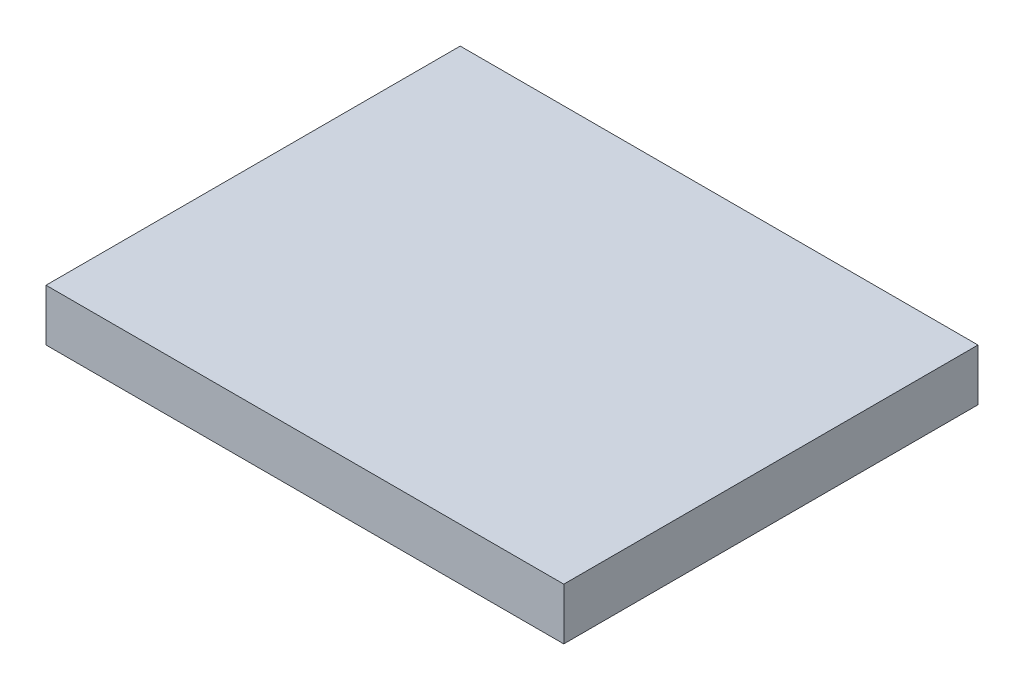
SolidWorks part; units mm, degrees
ref_plane "Front Plane" through (0, 0, 0) normal (0, 0, 1) x (1, 0, 0)
ref_plane "Top Plane" through (0, 0, 0) normal (0, 1, 0) x (1, 0, 0)
ref_plane "Right Plane" through (0, 0, 0) normal (1, 0, 0) x (0, 0, -1)
sketch "Sketch1" plane through (0, 0, 0) normal (0, 1, 0) x (1, 0, 0)
  line L1 (-25, 20) -> (25, 20)
  line L2 (-25, 20) -> (-25, -20)
  line L3 (-25, -20) -> (25, -20)
  line L4 (25, 20) -> (25, -20)
  line L5 (-25, 20) -> (25, -20) construction
  line L6 (-25, -20) -> (25, 20) construction
  point P0 (0, 0)
extrude "Boss-Extrude1" add sketch "Sketch1" along normal mid plane 5
